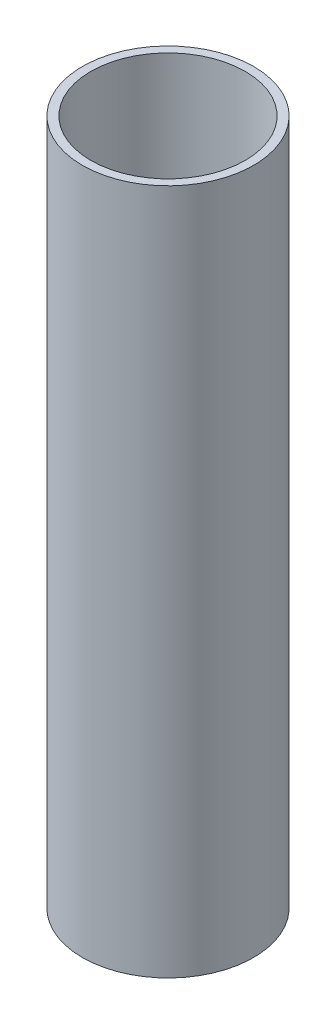
SolidWorks part; units mm, degrees
ref_plane "Front Plane" through (0, 0, 0) normal (0, 0, 1) x (1, 0, 0)
ref_plane "Top Plane" through (0, 0, 0) normal (0, 1, 0) x (1, 0, 0)
ref_plane "Right Plane" through (0, 0, 0) normal (1, 0, 0) x (0, 0, -1)
sketch "Sketch1" plane through (0, 0, 0) normal (0, 1, 0) x (1, 0, 0)
  circle A0 centre (0, 0) radius 50.7349
  circle A1 centre (0, 0) radius 45.72
extrude "Boss-Extrude1" add sketch "Sketch1" along normal blind 406.4
